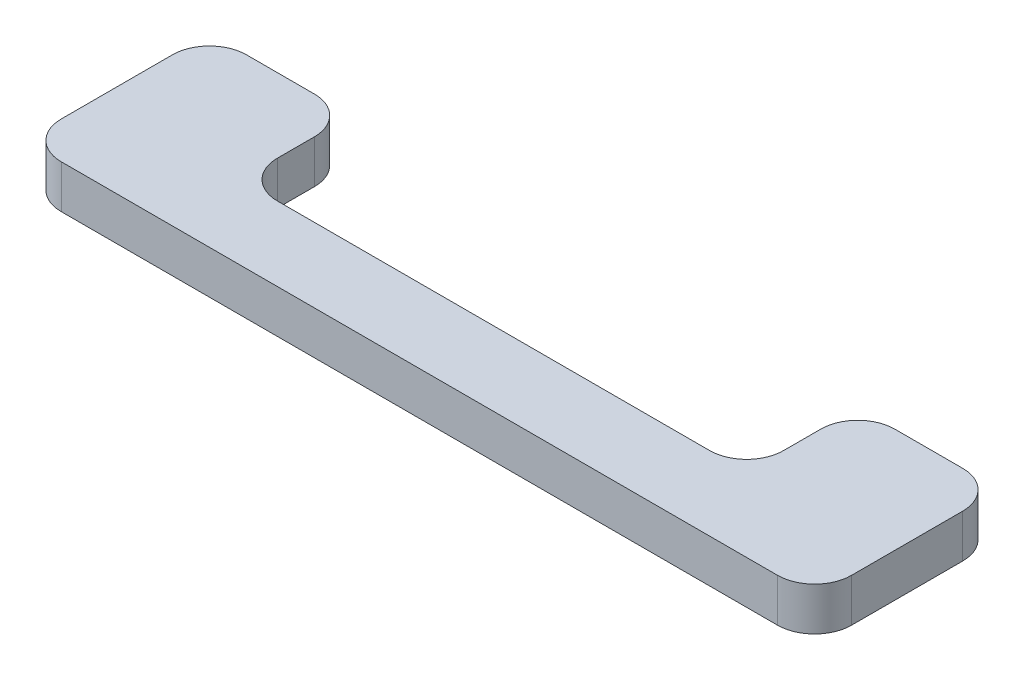
SolidWorks part; units mm, degrees
material "Q235"
ref_plane "前视基准面" through (0, 0, 0) normal (0, 0, 1) x (1, 0, 0)
ref_plane "上视基准面" through (0, 0, 0) normal (0, 1, 0) x (1, 0, 0)
ref_plane "右视基准面" through (0, 0, 0) normal (1, 0, 0) x (0, 0, -1)
sketch "草图1" plane through (0, 0, 0) normal (0, 1, 0) x (1, 0, 0)
  line L0 (205, 0) -> (-205, 0)
  line L1 (-205, 0) -> (-205, 90)
  line L2 (-205, 90) -> (-320, 90)
  line L3 (-320, 90) -> (-320, -60)
  line L4 (-320, -60) -> (320, -60)
  line L5 (0, -60) -> (0, 0) construction
  line L6 (320, 90) -> (320, -60)
  line L7 (205, 90) -> (320, 90)
  line L8 (205, 0) -> (205, 90)
  dimension "D1" = 60
  dimension "D2" = 115
  dimension "D3" = 320
  dimension "D4" = 150
extrude "凸台-拉伸1" add sketch "草图1" along normal blind 35
fillet "圆角1" radius 30 8 edges at (320, 17.5, 60) (320, 17.5, -90) (205, 17.5, -90) (205, 17.5, 0) (-205, 17.5, 0) (-320, 17.5, 60) (-320, 17.5, -90) (-205, 17.5, -90)
